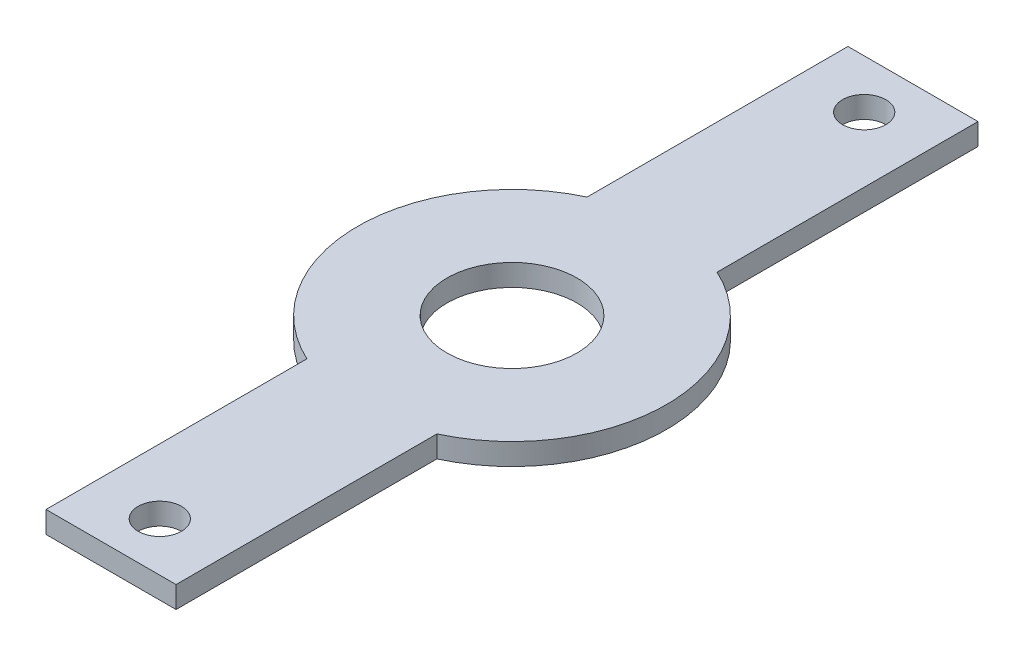
SolidWorks part; units mm, degrees
ref_plane "Front Plane" through (0, 0, 0) normal (0, 0, 1) x (1, 0, 0)
ref_plane "Top Plane" through (0, 0, 0) normal (0, 1, 0) x (1, 0, 0)
ref_plane "Right Plane" through (0, 0, 0) normal (1, 0, 0) x (0, 0, -1)
sketch "Sketch1" plane through (0, 0, 0) normal (0, 1, 0) x (1, 0, 0)
  line L0 (0, 0) -> (0, 37) construction
  line L1 (-6, 37) -> (6, 37)
  line L2 (6, 37) -> (6, 12.9253)
  line L3 (-6, 37) -> (-6, 12.9253)
  line L4 (0, 0) -> (6.7962, 0) construction
  line L5 (6, -37) -> (6, -12.9253)
  line L6 (-6, -37) -> (6, -37)
  line L7 (-6, -37) -> (-6, -12.9253)
  arc A0 (-6, 12.9253) -> (-6, -12.9253) centre (0, 0) ccw
  circle A1 centre (0, 22.5) radius 3.5 construction
  circle A2 centre (0, 32.5) radius 2
  circle A3 centre (0, -22.5) radius 3.5 construction
  circle A4 centre (0, -32.5) radius 2
  arc A5 (6, -12.9253) -> (6, 12.9253) centre (0, 0) ccw
  dimension "D1" = 28.5
  dimension "D2" = 7
  dimension "D4" = 4
  dimension "D3" = 22.5
  dimension "D5" = 10
  dimension "D6" = 37
  dimension "D7" = 6
extrude "Boss-Extrude1" add sketch "Sketch1" along normal blind 2
ref_plane "Plane1" through (0, 2, 0) normal (0, 1, 0) x (1, 0, 0)
sketch "Sketch2" plane through (0, 2, 0) normal (0, 1, 0) x (1, 0, 0)
  circle A0 centre (0, 0) radius 6
  dimension "D1" = 12
extrude "Cut-Extrude1" cut sketch "Sketch2" against normal up to next
